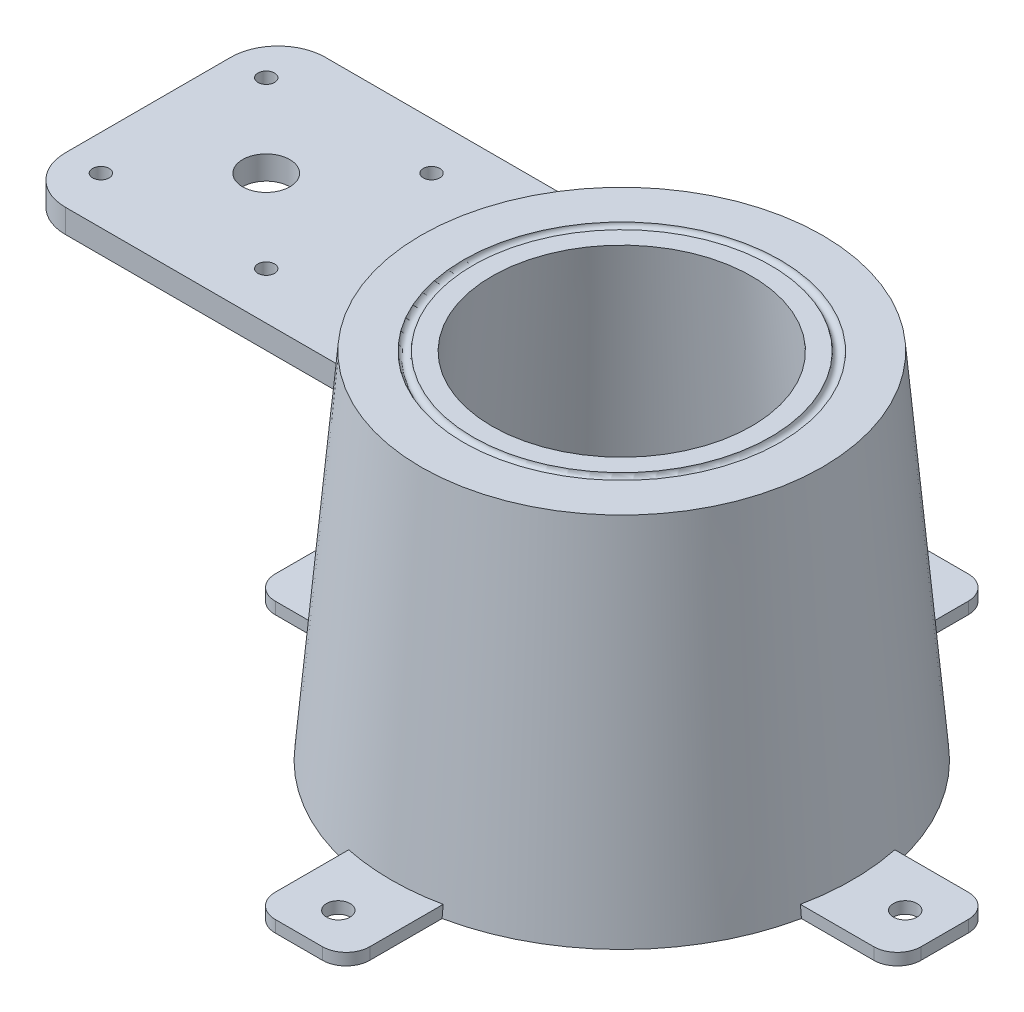
SolidWorks part; units mm, degrees
ref_plane "Front Plane" through (0, 0, 0) normal (0, 0, 1) x (1, 0, 0)
ref_plane "Top Plane" through (0, 0, 0) normal (0, 1, 0) x (1, 0, 0)
ref_plane "Right Plane" through (0, 0, 0) normal (1, 0, 0) x (0, 0, -1)
sketch "Sketch1" plane through (0, 0, 0) normal (0, 1, 0) x (1, 0, 0)
  circle A0 centre (0, 0) radius 55 construction
  circle A1 centre (0, 0) radius 85
  dimension "D1" = 110
  dimension "D2" = 30
extrude "Boss-Extrude1" add sketch "Sketch1" against normal blind 150 draft 5 draft outward yes
sketch "Sketch2" plane through (0, 0, 0) normal (0, 1, 0) x (1, 0, 0)
  circle A2 centre (0, 0) radius 55 construction
  circle A4 centre (0, 0) radius 55 construction
  circle A6 centre (0, 0) radius 65
  dimension "D1" = 10
sweep "Cut-Sweep1" cut path "Sketch2" circular profile diameter 4 parameters "D3"=4
sketch "Sketch11" plane through (0, 0, 0) normal (0, 1, 0) x (1, 0, 0)
  circle A0 centre (0, 0) radius 55 construction
  circle A1 centre (0, 0) radius 55
extrude "Cut-Extrude1" cut sketch "Sketch11" against normal up to surface (150 mm away) draft 5
sketch "Sketch13" plane through (0, 0, 0) normal (0, 1, 0) x (1, 0, 0)
  line L0 (0, 0) -> (-150.53, 0) construction
  line L2 (-200.53, 55) -> (-60.53, 55)
  line L3 (-200.53, 55) -> (-200.53, -55)
  line L4 (-200.53, -55) -> (-60.53, -55)
  line L5 (-60.53, 55) -> (-60.53, -55)
  circle A0 centre (0, 0) radius 85 construction
  circle A1 centre (0, 0) radius 85 construction
  dimension "D1" = 150.53
  dimension "D2" = 110
  dimension "D3" = 90
  dimension "D4" = 50
  dimension "D5" = 55
extrude "Boss-Extrude2" add sketch "Sketch13" against normal blind 10 from offset 10 offset against normal yes
sketch "Sketch14" plane through (0, -10, 0) normal (0, 1, 0) x (1, 0, 0)
  line L0 (0, 0) -> (-150.53, 0) construction
  line L1 (0, 0) -> (-150.53, 0)
  circle A0 centre (-150.53, 0) radius 10
  dimension "D1" = 20
extrude "Cut-Extrude2" cut sketch "Sketch14" against normal blind 10
fillet "Fillet3" radius 20 2 edges at (-200.53, -15, -55) (-200.53, -15, 55)
sketch "Sketch15" plane through (0, -10, 0) normal (0, 1, 0) x (1, 0, 0)
  line L0 (-150.53, 35) -> (-150.53, -35) construction
  line L1 (-185.53, 35) -> (-115.53, 35) construction
  line L2 (-185.53, 35) -> (-185.53, -35) construction
  line L3 (-185.53, -35) -> (-115.53, -35) construction
  line L4 (-115.53, 35) -> (-115.53, -35) construction
  line L5 (-185.53, 35) -> (-115.53, -35) construction
  line L6 (-185.53, -35) -> (-115.53, 35) construction
  line L7 (-185.53, 0) -> (-115.53, 0) construction
  circle A0 centre (-150.53, 0) radius 10 construction
  circle A1 centre (-150.53, 0) radius 10 construction
  circle A2 centre (-185.53, 35) radius 3.5
  circle A3 centre (-115.53, 35) radius 3.5
  circle A4 centre (-115.53, -35) radius 3.5
  circle A5 centre (-185.53, -35) radius 3.5
  dimension "D3" = 7
  dimension "D1" = 70
  dimension "D2" = 70
extrude "Cut-Extrude3" cut sketch "Sketch15" against normal up to surface (10 mm away) up to face at (-150.53, -20, 10)
sketch "Sketch17" plane through (0, -150, 0) normal (0, -1, 0) x (1, 0, 0)
  line L0 (0, 0) -> (0, 120) construction
  line L1 (-10, 136.6948) -> (10, 136.6948)
  line L2 (20, 126.6948) -> (20, 82.305)
  line L3 (-20, 126.6948) -> (-20, 82.305)
  line L4 (-20, 82.305) -> (20, 82.305)
  circle A0 centre (0, 120) radius 5
  arc A1 (20, 126.6948) -> (10, 136.6948) centre (10, 126.6948) ccw
  arc A2 (-20, 126.6948) -> (-10, 136.6948) centre (-10, 126.6948) cw
  point P9 (0, 136.6948)
  point P11 (20, 136.6948)
  point P14 (-20, 136.6948)
  dimension "D2" = 10
  dimension "D4" = 10
  dimension "D1" = 120
  dimension "D3" = 20
extrude "Boss-Extrude3" add sketch "Sketch17" against normal blind 5
pattern_circular "CirPattern1" count 4 over 360 about axis through (0, 0, 0) along (0, 1, 0) of "Boss-Extrude3"
